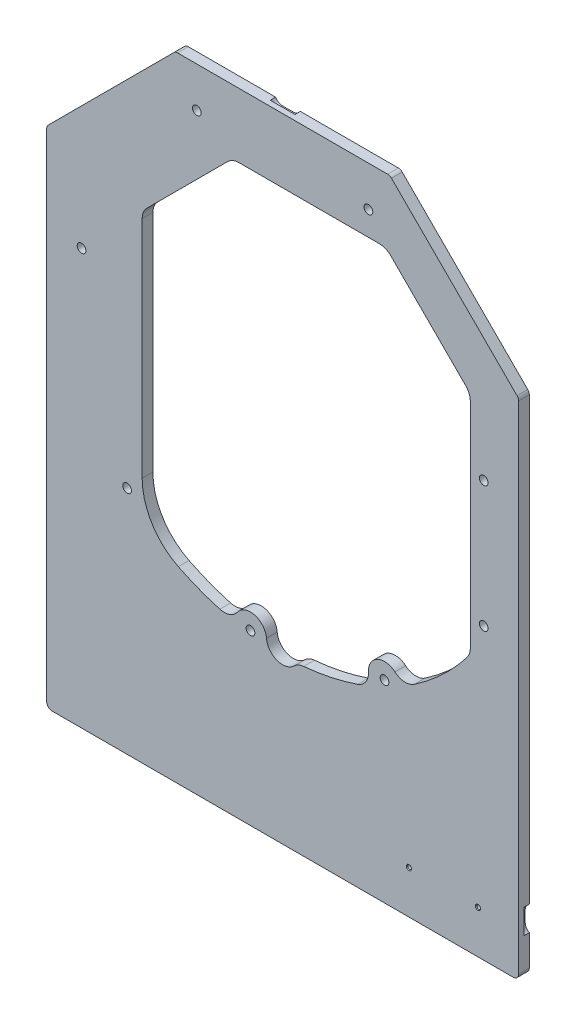
SolidWorks part; units mm, degrees
material "6061-T6 (SS)"
ref_plane "Front Plane" through (0, 0, 0) normal (0, 0, 1) x (1, 0, 0)
ref_plane "Top Plane" through (0, 0, 0) normal (0, 1, 0) x (1, 0, 0)
ref_plane "Right Plane" through (0, 0, 0) normal (1, 0, 0) x (0, 0, -1)
sketch "Sketch1" plane through (0, 0, 0) normal (0, 0, 1) x (1, 0, 0)
  line L0 (63.5, 139.7) -> (139.7, 63.5)
  line L1 (-63.5, 139.7) -> (63.5, 139.7)
  line L2 (-139.7, 63.5) -> (-139.7, -234.95)
  line L3 (-139.7, -234.95) -> (139.7, -234.95)
  line L4 (139.7, 63.5) -> (139.7, -234.95)
  line L5 (-63.5, 139.7) -> (-139.7, 63.5)
  line L6 (-32.5478, 98.8102) -> (-80.3922, 50.9658)
  line L7 (-83.182, -88.9) -> (-83.182, 44.2306)
  line L8 (-25.8126, 101.6) -> (57.2435, 101.6)
  line L9 (63.9787, 98.8102) -> (108.3352, 54.4537)
  line L10 (111.125, 47.7185) -> (111.125, -78.8381)
  arc A0 (109.1252, -84.6774) -> (78.0231, -113.9779) centre (0, 0) cw
  arc A1 (-61.7715, -123.5429) -> (-83.182, -88.9) centre (-44.45, -88.9) cw
  arc A2 (78.0231, -113.9779) -> (66.4839, -113.384) centre (72.6427, -106.1181) cw
  arc A3 (66.4839, -113.384) -> (50.8169, -121.2175) centre (60.325, -120.65) ccw
  arc A4 (50.8169, -121.2175) -> (44.3685, -130.8052) centre (41.3088, -121.785) cw
  arc A5 (44.3685, -130.8052) -> (12.4763, -137.5606) centre (0, 0) cw
  arc A6 (6.6917, -140.2224) -> (12.4763, -137.5606) centre (13.3366, -147.0466) cw
  arc A8 (-80.3922, 50.9658) -> (-83.182, 44.2306) centre (-73.657, 44.2306) ccw
  arc A9 (-25.8126, 101.6) -> (-32.5478, 98.8102) centre (-25.8126, 92.075) ccw
  arc A10 (57.2435, 101.6) -> (63.9787, 98.8102) centre (57.2435, 92.075) cw
  arc A11 (108.3352, 54.4537) -> (111.125, 47.7185) centre (101.6, 47.7185) cw
  arc A12 (111.125, -78.8381) -> (109.1252, -84.6774) centre (101.6, -78.8381) cw
  arc A13 (-37.1555, -133.034) -> (-26.7854, -129.3924) centre (-34.5753, -123.7954) ccw
  arc A14 (-26.7854, -129.3924) -> (-9.5584, -134.1529) centre (-19.05, -134.9502) cw
  arc A15 (-9.5584, -134.1529) -> (6.6917, -140.2224) centre (0, -133.35) ccw
  circle A17 centre (69.85, -82.55) radius 27.94 construction
  circle A18 centre (-52.4111, -95.0268) radius 18.9564 construction
  arc A19 (-37.1555, -133.034) -> (-61.7715, -123.5429) centre (0, 0) cw
  dimension "D5" = 44.45
  dimension "D10" = 9.525
  dimension "D11" = 38.732
  dimension "D15" = 138.1252
  dimension "D21" = 134.9502
  dimension "D22" = 19.05
  dimension "D23" = 1.6002
  dimension "D25" = 9.525
  dimension "D26" = 9.525
  dimension "D27" = 9.525
  dimension "D34" = 82.55
  dimension "D32" = 9.5921
  dimension "D33" = 9.525
  dimension "D35" = 69.85
  dimension "D24" = 55.88
  dimension "D1" = 234.95
  dimension "D2" = 139.7
  dimension "D3" = 139.7
  dimension "D4" = 139.7
  dimension "D6" = 45
  dimension "D7" = 45
  dimension "D8" = 76.2
  dimension "D9" = 88.9
  dimension "D12" = 101.6
  dimension "D13" = 28.575
  dimension "D14" = 28.575
  dimension "D16" = 63.5
  dimension "D17" = 107.7631
  dimension "D18" = 127
  dimension "D19" = 120.65
  dimension "D20" = 60.325
  dimension "D28" = 56.518
  dimension "D29" = 50.8
extrude "Boss-Extrude1" add sketch "Sketch1" against normal blind 6.35
hole_wizard "13/64 (0.20313) Diameter Hole1" positions "Sketch9" profile "Sketch8" hole size "13/64" standard "Ansi Inch" end condition through all
sketch "Sketch9" plane through (-107.95, -107.95, 0) normal (0, 0, 1) x (1, 0, 0)
  point P1 (158.75, 223.8502)
  point P3 (57.15, 223.8502)
  point P14 (227.0252, 119.0752)
  point P18 (-11.1252, 119.0752)
  point P19 (227.0252, 44.45)
  point P23 (168.275, -12.7)
  point P25 (88.9, -27.0002)
  point P27 (15.875, 9.525)
  dimension "D1" = 115.9002
  dimension "D2" = 63.5
  dimension "D3" = 50.8
  dimension "D4" = 50.8
  dimension "D5" = 11.1252
  dimension "D6" = 119.0752
  dimension "D7" = 119.0752
  dimension "D8" = 11.1252
  dimension "D9" = 98.425
  dimension "D10" = 92.075
sketch "Sketch8" plane through (50.8, 115.9002, 0) normal (1, 0, 0) x (0, -1, 0)
  line L0 (0, 0) -> (0, 6.35)
  line L1 (0, 6.35) -> (2.5798, 6.35)
  line L2 (2.5798, 6.35) -> (2.5798, 0)
  line L5 (2.5798, 0) -> (0, 0)
  line L11 (0, -6.35) -> (0, 107.95) construction
  dimension "Thru Hole Dia." = 5.1595
  dimension "Thru Hole Depth" = 6.35
fillet "Fillet1" radius 3.175 6 edges at (-63.5, 139.7, -3.175) (139.7, 63.5, -3.175) (-139.7, 63.5, -3.175) (63.5, 139.7, -3.175) (139.7, -234.95, -3.175) (-139.7, -234.95, -3.175)
sketch "Sketch10 For Machine Hold Down" plane through (0, 0, -6.35) normal (0, 0, -1) x (-1, 0, 0)
  circle A0 centre (-16.9019, 82.55) radius 2.5798
  circle A1 centre (-16.9019, -123.825) radius 2.5798
  circle A2 centre (19.05, -134.9502) radius 2.5798 construction
  dimension "D1" = 123.825
  dimension "D2" = 82.55
  dimension "D3" = 16.9019
sketch "Sketch11" plane through (0, 0, -6.35) normal (0, 0, -1) x (-1, 0, 0)
  line L0 (-139.7, 63.5) -> (-139.7, -234.95) construction
  line L1 (-177.0796, -198.4248) -> (-142.0622, -198.4248)
  line L2 (-177.0796, -198.4248) -> (-177.0796, -214.2998)
  line L3 (-177.0796, -214.2998) -> (-142.0622, -214.2998)
  line L4 (-137.287, -203.2) -> (-137.287, -209.5246)
  line L5 (-4.7498, 156.3597) -> (11.1252, 156.3597)
  line L6 (-4.7498, 156.3597) -> (-4.7498, 142.0622)
  line L7 (0.0254, 137.287) -> (6.35, 137.287)
  line L8 (11.1252, 156.3597) -> (11.1252, 142.0622)
  line L9 (139.7, -234.95) -> (-139.7, -234.95) construction
  line L10 (63.5, 139.7) -> (-63.5, 139.7) construction
  arc A0 (-142.0622, -198.4248) -> (-137.287, -203.2) centre (-142.0622, -203.2) cw
  arc A1 (-142.0622, -214.2998) -> (-137.287, -209.5246) centre (-142.0622, -209.5246) ccw
  arc A2 (6.35, 137.287) -> (11.1252, 142.0622) centre (6.35, 142.0622) ccw
  arc A3 (-4.7498, 142.0622) -> (0.0254, 137.287) centre (0.0254, 142.0622) ccw
  dimension "D1" = 4.7752
  dimension "D5" = 4.7752
  dimension "D2" = 15.875
  dimension "D3" = 2.413
  dimension "D4" = 20.6502
  dimension "D6" = 15.875
  dimension "D7" = 2.413
  dimension "D8" = 11.1252
extrude "Cut-Extrude1" cut sketch "Sketch11" against normal blind 3.175
sketch "Sketch12" plane through (0, 0, 0) normal (0, 0, 1) x (1, 0, 0)
  line L0 (78.5749, -217.8685) -> (111.9251, -217.8685)
  line L1 (111.9251, -201.2315) -> (78.5749, -201.2315)
  line L2 (-139.7, -234.95) -> (139.7, -234.95) construction
  line L4 (95.25, -201.2315) -> (95.25, -209.55) construction
  line L5 (139.7, 63.5) -> (139.7, -234.95) construction
  arc A0 (111.9251, -217.8685) -> (111.9251, -201.2315) centre (111.9251, -209.55) ccw
  arc A1 (78.5749, -201.2315) -> (78.5749, -217.8685) centre (78.5749, -209.55) ccw
  dimension "D2" = 49.9872
  dimension "D3" = 44.45
  dimension "D1" = 25.4
  dimension "D4" = 16.637
hole_wizard "#4-40 Tapped Hole1" positions "Sketch15" profile "Sketch14" tap size "#4-40" standard "Ansi Inch" end condition through all
sketch "Sketch15" plane through (-70.0915, 24.6733, 0) normal (0, 0, 1) x (1, 0, 0)
  line L0 (165.3415, -225.9048) -> (165.3415, -234.2233) construction
  point P0 (185.7758, -234.2233)
  point P1 (144.8945, -234.2233)
  dimension "D1" = 20.4343
  dimension "D2" = 20.447
sketch "Sketch14" plane through (115.6843, -209.55, 0) normal (1, 0, 0) x (0, -1, 0)
  line L0 (0, 0) -> (0, 6.35)
  line L1 (0, 6.35) -> (1.651, 6.35)
  line L2 (1.1303, 5.8293) -> (1.1303, 0.3937)
  line L3 (1.1303, 0.3937) -> (1.524, 0)
  line L5 (1.524, 0) -> (0, 0)
  line L6 (-1.1303, 0.3937) -> (-1.524, 0) construction
  line L7 (1.651, 6.35) -> (1.1303, 5.8293)
  line L8 (-1.651, 6.35) -> (-1.1303, 5.8293) construction
  line L11 (0, -6.35) -> (0, 107.95) construction
  dimension "Thread Major Dia." = 2.2606
  dimension "Thru Tap Drill Depth" = 6.35
  dimension "Near C'Sink Dia." = 3.048
  dimension "Near C'Sink Angle" = 90
  dimension "Far C'Sink Dia." = 3.302
  dimension "Far C'Sink Angle" = 90
extrude "Cut-Extrude2" [suppressed] cut sketch "Sketch12" against normal blind 1.016
